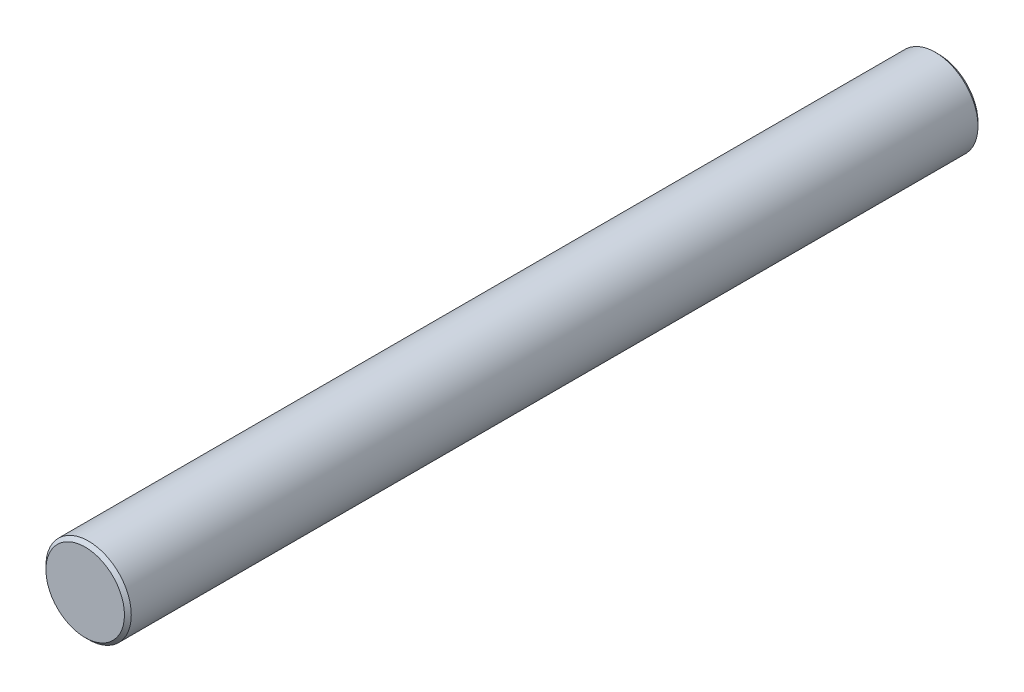
SolidWorks part; units mm, degrees
ref_plane "Ebene vorne" through (0, 0, 0) normal (0, 0, 1) x (1, 0, 0)
ref_plane "Ebene oben" through (0, 0, 0) normal (0, 1, 0) x (1, 0, 0)
ref_plane "Ebene rechts" through (0, 0, 0) normal (1, 0, 0) x (0, 0, -1)
sketch "Skizze1" plane through (0, 0, 0) normal (0, 0, 1) x (1, 0, 0)
  circle A0 centre (0, 0) radius 5
  dimension "D1" = 10
extrude "Aufsatz-Linear austragen1" add sketch "Skizze1" along normal blind 100
chamfer "Fase1" distance 0.4 angle 45 2 edges at (5, 0, 0) (5, 0, 100)
